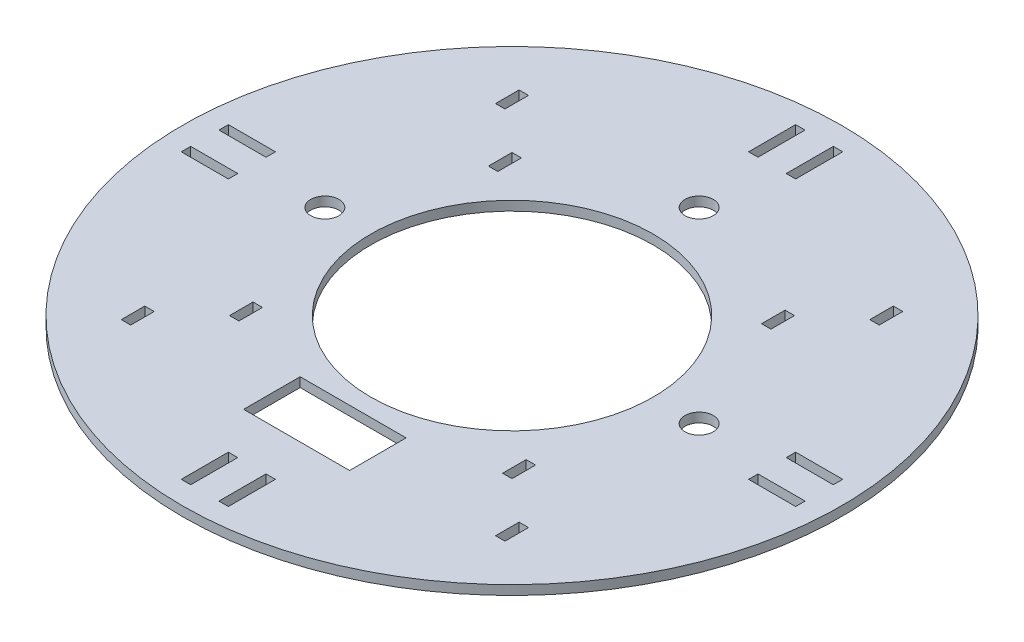
SolidWorks part; units mm, degrees
material "Thornel Mat VMA"
ref_plane "Front Plane" through (0, 0, 0) normal (0, 0, 1) x (1, 0, 0)
ref_plane "Top Plane" through (0, 0, 0) normal (0, 1, 0) x (1, 0, 0)
ref_plane "Right Plane" through (0, 0, 0) normal (1, 0, 0) x (0, 0, -1)
sketch "Sketch1" plane through (0, 0, 0) normal (0, 1, 0) x (1, 0, 0)
  line L0 (-49.4975, 49.4975) -> (-30, 30) construction
  line L1 (-52.2487, 5) -> (-67.2487, 5) construction
  line L2 (-67.2487, 5) -> (-67.2487, -5) construction
  line L3 (-67.2487, -5) -> (-52.2487, -5) construction
  line L4 (-52.2487, -5) -> (-52.2487, 5) construction
  line L5 (-30, -30) -> (30, 30) construction
  line L6 (-30, 30) -> (30, -30) construction
  line L7 (-30, 30) -> (-28, 30)
  line L8 (-30, 30) -> (-30, 25)
  line L9 (-30, 25) -> (-28, 25)
  line L10 (-28, 30) -> (-28, 25)
  line L11 (30, 30) -> (28, 30)
  line L12 (30, 30) -> (30, 25)
  line L13 (30, 25) -> (28, 25)
  line L14 (28, 30) -> (28, 25)
  line L15 (-30, -30) -> (-28, -30)
  line L16 (-30, -30) -> (-30, -25)
  line L17 (-30, -25) -> (-28, -25)
  line L18 (-28, -30) -> (-28, -25)
  line L19 (30, -30) -> (28, -30)
  line L20 (30, -30) -> (30, -25)
  line L21 (30, -25) -> (28, -25)
  line L22 (28, -30) -> (28, -25)
  line L23 (30, 30) -> (49.4975, 49.4975) construction
  line L24 (-49.4975, -49.4975) -> (-30, -30) construction
  line L25 (-30, -30) -> (-30, 30) construction
  line L26 (-30, 30) -> (30, 30) construction
  line L27 (30, 30) -> (30, -30) construction
  line L28 (30, -30) -> (30.057, -29.7836) construction
  line L29 (49.4975, -49.4975) -> (30, -30) construction
  line L30 (0, 49.4975) -> (0, 70) construction
  line L31 (-40.7487, 42.2487) -> (-38.7487, 42.2487)
  line L32 (-40.7487, 42.2487) -> (-40.7487, 37.2487)
  line L33 (-40.7487, 37.2487) -> (-38.7487, 37.2487)
  line L34 (-38.7487, 42.2487) -> (-38.7487, 37.2487)
  line L35 (-40.7487, 42.2487) -> (-38.7487, 37.2487) construction
  line L36 (-40.7487, 37.2487) -> (-38.7487, 42.2487) construction
  line L37 (38.7487, 42.2487) -> (40.7487, 42.2487)
  line L38 (38.7487, 42.2487) -> (38.7487, 37.2487)
  line L39 (38.7487, 37.2487) -> (40.7487, 37.2487)
  line L40 (40.7487, 42.2487) -> (40.7487, 37.2487)
  line L41 (38.7487, 42.2487) -> (40.7487, 37.2487) construction
  line L42 (38.7487, 37.2487) -> (40.7487, 42.2487) construction
  line L43 (38.7487, -37.2487) -> (40.7487, -37.2487)
  line L44 (38.7487, -37.2487) -> (38.7487, -42.2487)
  line L45 (38.7487, -42.2487) -> (40.7487, -42.2487)
  line L46 (40.7487, -37.2487) -> (40.7487, -42.2487)
  line L47 (38.7487, -37.2487) -> (40.7487, -42.2487) construction
  line L48 (38.7487, -42.2487) -> (40.7487, -37.2487) construction
  line L49 (-40.7487, -37.2487) -> (-38.7487, -37.2487)
  line L50 (-40.7487, -37.2487) -> (-40.7487, -42.2487)
  line L51 (-40.7487, -42.2487) -> (-38.7487, -42.2487)
  line L52 (-38.7487, -37.2487) -> (-38.7487, -42.2487)
  line L53 (-40.7487, -37.2487) -> (-38.7487, -42.2487) construction
  line L54 (-40.7487, -42.2487) -> (-38.7487, -37.2487) construction
  line L55 (-49.4975, 0) -> (-70, 0) construction
  line L56 (49.4975, 0) -> (70, 0) construction
  line L57 (0, -49.4975) -> (0, -70) construction
  line L58 (-49.4975, 0) -> (-30, 0) construction
  line L60 (-11.25, -33.7487) -> (11.25, -33.7487)
  line L61 (-11.25, -33.7487) -> (-11.25, -45.7487)
  line L62 (-11.25, -45.7487) -> (11.25, -45.7487)
  line L63 (-5, 52.2487) -> (5, 67.2487) construction
  line L64 (-5, 67.2487) -> (5, 52.2487) construction
  line L65 (-5, 52.2487) -> (5, 52.2487) construction
  line L66 (5, 52.2487) -> (5, 67.2487) construction
  line L67 (5, 67.2487) -> (-5, 67.2487) construction
  line L68 (-5, 67.2487) -> (-5, 52.2487) construction
  line L69 (52.2487, -5) -> (67.2487, 5) construction
  line L70 (52.2487, 5) -> (67.2487, -5) construction
  line L71 (52.2487, -5) -> (67.2487, -5) construction
  line L72 (67.2487, -5) -> (67.2487, 5) construction
  line L73 (67.2487, 5) -> (52.2487, 5) construction
  line L74 (52.2487, 5) -> (52.2487, -5) construction
  line L75 (-5, -52.2487) -> (5, -67.2487) construction
  line L76 (-5, -67.2487) -> (5, -52.2487) construction
  line L77 (-5, -52.2487) -> (5, -52.2487) construction
  line L78 (5, -52.2487) -> (5, -67.2487) construction
  line L79 (5, -67.2487) -> (-5, -67.2487) construction
  line L80 (-5, -67.2487) -> (-5, -52.2487) construction
  line L81 (-67.2487, 5) -> (-52.2487, -5) construction
  line L82 (-67.2487, -5) -> (-52.2487, 5) construction
  line L83 (-67.2487, 5) -> (-62.2487, 5)
  line L84 (-67.2487, 5) -> (-67.2487, 3)
  line L85 (-67.2487, 3) -> (-62.2487, 3)
  line L86 (-62.2487, 5) -> (-62.2487, 3)
  line L87 (-67.2487, -5) -> (-62.2487, -5)
  line L88 (-67.2487, -5) -> (-67.2487, -3)
  line L89 (-67.2487, -3) -> (-62.2487, -3)
  line L90 (-62.2487, -5) -> (-62.2487, -3)
  line L91 (-52.2487, -5) -> (-57.2487, -5)
  line L92 (-52.2487, -5) -> (-52.2487, -3)
  line L93 (-52.2487, -3) -> (-57.2487, -3)
  line L94 (-57.2487, -5) -> (-57.2487, -3)
  line L95 (-52.2487, 5) -> (-57.2487, 5)
  line L96 (-52.2487, 5) -> (-52.2487, 3)
  line L97 (-52.2487, 3) -> (-57.2487, 3)
  line L98 (-57.2487, 5) -> (-57.2487, 3)
  line L99 (-5, 67.2487) -> (-3, 67.2487)
  line L100 (-5, 67.2487) -> (-5, 62.2487)
  line L101 (-5, 62.2487) -> (-3, 62.2487)
  line L102 (-3, 67.2487) -> (-3, 62.2487)
  line L103 (-5, 52.2487) -> (-3, 52.2487)
  line L104 (-5, 52.2487) -> (-5, 57.2487)
  line L105 (-5, 57.2487) -> (-3, 57.2487)
  line L106 (-3, 52.2487) -> (-3, 57.2487)
  line L107 (5, 52.2487) -> (3, 52.2487)
  line L108 (5, 52.2487) -> (5, 57.2487)
  line L109 (5, 57.2487) -> (3, 57.2487)
  line L110 (3, 52.2487) -> (3, 57.2487)
  line L111 (5, 67.2487) -> (3, 67.2487)
  line L112 (5, 67.2487) -> (5, 62.2487)
  line L113 (5, 62.2487) -> (3, 62.2487)
  line L114 (3, 67.2487) -> (3, 62.2487)
  line L115 (52.2487, 5) -> (57.2487, 5)
  line L116 (52.2487, 5) -> (52.2487, 3)
  line L117 (52.2487, 3) -> (57.2487, 3)
  line L118 (57.2487, 5) -> (57.2487, 3)
  line L119 (52.2487, -5) -> (57.2487, -5)
  line L120 (52.2487, -5) -> (52.2487, -3)
  line L121 (52.2487, -3) -> (57.2487, -3)
  line L122 (57.2487, -5) -> (57.2487, -3)
  line L123 (67.2487, 5) -> (62.2487, 5)
  line L124 (67.2487, 5) -> (67.2487, 3)
  line L125 (67.2487, 3) -> (62.2487, 3)
  line L126 (62.2487, 5) -> (62.2487, 3)
  line L127 (67.2487, -5) -> (62.2487, -5)
  line L128 (67.2487, -5) -> (67.2487, -3)
  line L129 (67.2487, -3) -> (62.2487, -3)
  line L130 (62.2487, -5) -> (62.2487, -3)
  line L131 (-5, -52.2487) -> (-3, -52.2487)
  line L132 (-5, -52.2487) -> (-5, -57.2487)
  line L133 (-5, -57.2487) -> (-3, -57.2487)
  line L134 (-3, -52.2487) -> (-3, -57.2487)
  line L135 (5, -52.2487) -> (3, -52.2487)
  line L136 (5, -52.2487) -> (5, -57.2487)
  line L137 (5, -57.2487) -> (3, -57.2487)
  line L138 (3, -52.2487) -> (3, -57.2487)
  line L139 (5, -67.2487) -> (3, -67.2487)
  line L140 (5, -67.2487) -> (5, -62.2487)
  line L141 (5, -62.2487) -> (3, -62.2487)
  line L142 (3, -67.2487) -> (3, -62.2487)
  line L143 (-5, -67.2487) -> (-3, -67.2487)
  line L144 (-5, -67.2487) -> (-5, -62.2487)
  line L145 (-5, -62.2487) -> (-3, -62.2487)
  line L146 (-3, -67.2487) -> (-3, -62.2487)
  line L147 (0, 49.4975) -> (0, 30) construction
  line L148 (30, 0) -> (49.4975, 0) construction
  line L149 (0, -30) -> (0, -49.4975) construction
  line L150 (-49.4975, -49.4975) -> (-49.4975, 49.4975) construction
  line L151 (-49.4975, 49.4975) -> (49.4975, 49.4975) construction
  line L152 (49.4975, 49.4975) -> (49.4975, -49.4975) construction
  line L153 (49.4975, -49.4975) -> (-49.4975, -49.4975) construction
  line L154 (-30, -30) -> (30, -30) construction
  line L155 (-52.2487, 5) -> (-67.2487, 5) construction
  line L156 (11.25, -33.7487) -> (11.25, -45.7487)
  line L157 (-11.25, -33.7487) -> (11.25, -45.7487) construction
  line L158 (-11.25, -45.7487) -> (11.25, -33.7487) construction
  circle A0 centre (0, 0) radius 30
  circle A1 centre (0, 0) radius 70
  circle A2 centre (0, -39.7487) radius 3
  circle A3 centre (39.7487, 0) radius 3
  circle A4 centre (-39.7487, 0) radius 3
  circle A5 centre (0, 39.7487) radius 3
  point P20 (-39.7487, 39.7487)
  point P29 (39.7487, 39.7487)
  point P34 (39.7487, -39.7487)
  point P39 (-39.7487, -39.7487)
  point P52 (0, 59.7487)
  point P57 (59.7487, 0)
  point P62 (0, -59.7487)
  point P67 (-59.7487, 0)
  dimension "D1" = 60
  dimension "D2" = 140
  dimension "D65" = 6
  dimension "D66" = 6
  dimension "D67" = 6
  dimension "D68" = 6
  dimension "D3" = 60
  dimension "D4" = 60
  dimension "D5" = 5
  dimension "D6" = 2
  dimension "D7" = 5
  dimension "D8" = 2
  dimension "D9" = 2
  dimension "D10" = 5
  dimension "D11" = 2
  dimension "D12" = 5
  dimension "D13" = 5
  dimension "D14" = 2
  dimension "D15" = 5
  dimension "D16" = 2
  dimension "D17" = 2
  dimension "D18" = 5
  dimension "D19" = 2
  dimension "D20" = 5
  dimension "D21" = 20.5025
  dimension "D22" = 15
  dimension "D23" = 10
  dimension "D24" = 20.5025
  dimension "D25" = 15
  dimension "D26" = 10
  dimension "D27" = 20.5025
  dimension "D28" = 15
  dimension "D29" = 10
  dimension "D30" = 20.5025
  dimension "D31" = 15
  dimension "D32" = 10
  dimension "D33" = 5
  dimension "D34" = 2
  dimension "D35" = 5
  dimension "D36" = 2
  dimension "D37" = 5
  dimension "D38" = 2
  dimension "D39" = 5
  dimension "D40" = 5
  dimension "D41" = 5
  dimension "D42" = 5
  dimension "D43" = 5
  dimension "D44" = 2
  dimension "D45" = 2
  dimension "D46" = 2
  dimension "D47" = 2
  dimension "D48" = 5
  dimension "D49" = 5
  dimension "D50" = 5
  dimension "D51" = 5
  dimension "D52" = 2
  dimension "D53" = 2
  dimension "D54" = 2
  dimension "D55" = 2
  dimension "D56" = 2
  dimension "D57" = 5
  dimension "D58" = 5
  dimension "D59" = 2
  dimension "D60" = 2
  dimension "D61" = 2
  dimension "D62" = 5
  dimension "D63" = 5
  dimension "D64" = 2
  dimension "D69" = 19.4975
  dimension "D70" = 22.5
  dimension "D71" = 12
extrude "Yükseklik-Ekstrüzyon1" add sketch "Sketch1" along normal blind 2 contours A1 A5 A4 A3 L60 L156 L62 L61 L146 L143 L144 L145 L131 L134 L133 L132 L115 L118 L117 L116 L114 L111 L112 L113 L99 L102 L101 L100 L98 L95 L96 L97 L83 L86 L85 L84 L43 L46 L45
sketch "Sketch2" plane through (0, 2, 0) normal (0, 1, 0) x (1, 0, 0)
  line L0 (-52.2487, 5) -> (-52.2487, 21.5478)
  line L1 (-52.2487, 21.5478) -> (-52.2487, -8.4522)
  dimension "D1" = 30
sketch "Sketch3" plane through (0, 2, 0) normal (0, 1, 0) x (1, 0, 0)
  line L0 (-65.2487, 5) -> (-55.2487, 5)
  line L1 (-67.2487, 5) -> (-62.2487, 5) construction
  line L2 (-52.2487, 5) -> (-57.2487, 5) construction
  line L3 (-65.2487, 3) -> (-55.2487, 3)
  line L4 (-67.2487, 3) -> (-62.2487, 3) construction
  line L5 (-52.2487, 3) -> (-57.2487, 3) construction
  line L6 (-55.2487, 3) -> (-55.2487, 5)
  line L7 (-55.2487, 5) -> (-55.2081, 4.9702)
  line L8 (-65.2487, 3) -> (-65.2487, 5)
  line L10 (-55.2487, 5) -> (-52.2487, 5)
  line L11 (-55.2487, 5) -> (-55.2487, 3)
  line L12 (-55.2487, 3) -> (-52.2487, 3)
  line L13 (-52.2487, 5) -> (-52.2487, 3)
  line L14 (-65.2487, 5) -> (-67.2487, 5)
  line L15 (-65.2487, 5) -> (-65.2487, 3)
  line L16 (-65.2487, 3) -> (-67.2487, 3)
  line L17 (-67.2487, 5) -> (-67.2487, 3)
  dimension "D1" = 2
  dimension "D2" = 10
extrude "Boss-Extrude1" add sketch "Sketch3" against normal blind 2
sketch "Sketch5" plane through (0, 2, 0) normal (0, 1, 0) x (1, 0, 0)
  line L1 (-62.2487, 5) -> (-57.2487, 5)
  line L2 (-62.2487, 5) -> (-62.2487, 3)
  line L3 (-62.2487, 3) -> (-57.2487, 3)
  line L4 (-57.2487, 5) -> (-57.2487, 3)
extrude "Cut-Extrude1" cut sketch "Sketch5" against normal blind 2
sketch "Sketch6" plane through (0, 2, 0) normal (0, 1, 0) x (1, 0, 0)
  line L0 (-67.2487, -3) -> (-62.2487, -3) construction
  line L1 (-65.2487, -3) -> (-55.2487, -3)
  line L2 (-65.2487, -3) -> (-65.2487, -5)
  line L3 (-65.2487, -5) -> (-55.2487, -5)
  line L4 (-55.2487, -3) -> (-55.2487, -5)
  line L5 (-52.2487, -5) -> (-57.2487, -5) construction
  line L6 (-67.2487, -5) -> (-67.2487, -3) construction
  line L8 (-65.2487, -3) -> (-67.2487, -3)
  line L9 (-65.2487, -3) -> (-65.2487, -5)
  line L10 (-65.2487, -5) -> (-67.2487, -5)
  line L11 (-67.2487, -3) -> (-67.2487, -5)
  line L12 (-55.2487, -3) -> (-52.2487, -3)
  line L13 (-55.2487, -3) -> (-55.2487, -5)
  line L14 (-55.2487, -5) -> (-52.2487, -5)
  line L15 (-52.2487, -3) -> (-52.2487, -5)
  dimension "D1" = 10
  dimension "D2" = 2
extrude "Boss-Extrude3" add sketch "Sketch6" against normal blind 2 contours L8 L11 L10 L2 | L15 L12 L4 L14
sketch "Sketch8" plane through (0, 2, 0) normal (0, 1, 0) x (1, 0, 0)
  line L1 (-62.2487, -3) -> (-57.2487, -3)
  line L2 (-62.2487, -3) -> (-62.2487, -5)
  line L3 (-62.2487, -5) -> (-57.2487, -5)
  line L4 (-57.2487, -3) -> (-57.2487, -5)
extrude "Cut-Extrude2" cut sketch "Sketch8" against normal blind 2
sketch "Sketch9" plane through (0, 2, 0) normal (0, 1, 0) x (1, 0, 0)
  line L0 (3, 67.2487) -> (3, 62.2487) construction
  line L1 (3, 65.2487) -> (5, 65.2487)
  line L2 (3, 65.2487) -> (3, 55.2487)
  line L3 (3, 55.2487) -> (5, 55.2487)
  line L4 (5, 65.2487) -> (5, 55.2487)
  line L5 (5, 52.2487) -> (5, 57.2487) construction
  line L6 (5, 67.2487) -> (3, 67.2487) construction
  line L8 (5, 55.2487) -> (3, 55.2487)
  line L9 (5, 55.2487) -> (5, 52.2487)
  line L10 (5, 52.2487) -> (3, 52.2487)
  line L11 (3, 55.2487) -> (3, 52.2487)
  line L12 (5, 65.2487) -> (3, 65.2487)
  line L13 (5, 65.2487) -> (5, 67.2487)
  line L14 (5, 67.2487) -> (3, 67.2487)
  line L15 (3, 65.2487) -> (3, 67.2487)
  dimension "D1" = 2
  dimension "D2" = 10
extrude "Boss-Extrude4" add sketch "Sketch9" against normal blind 2 contours L15 L1 L13 L14 | L3 L11 L10 L9
sketch "Sketch10" plane through (0, 2, 0) normal (0, 1, 0) x (1, 0, 0)
  line L0 (-5, 67.2487) -> (-5, 62.2487) construction
  line L1 (3, 62.2487) -> (5, 62.2487)
  line L2 (3, 62.2487) -> (3, 57.2487)
  line L3 (3, 57.2487) -> (5, 57.2487)
  line L4 (5, 62.2487) -> (5, 57.2487)
  line L5 (-5, 65.2487) -> (-3, 65.2487)
  line L6 (-5, 65.2487) -> (-5, 55.2487)
  line L7 (-5, 55.2487) -> (-3, 55.2487)
  line L8 (-3, 65.2487) -> (-3, 55.2487)
  line L9 (-3, 52.2487) -> (-3, 57.2487) construction
  line L10 (-5, 67.2487) -> (-3, 67.2487) construction
  line L12 (-3, 55.2487) -> (-5, 55.2487)
  line L13 (-3, 55.2487) -> (-3, 52.2487)
  line L14 (-3, 52.2487) -> (-5, 52.2487)
  line L15 (-5, 55.2487) -> (-5, 52.2487)
  line L16 (-3, 65.2487) -> (-5, 65.2487)
  line L17 (-3, 65.2487) -> (-3, 67.2487)
  line L18 (-3, 67.2487) -> (-5, 67.2487)
  line L19 (-5, 65.2487) -> (-5, 67.2487)
  dimension "D1" = 2
  dimension "D2" = 10
extrude "Boss-Extrude5" add sketch "Sketch10" against normal blind 2 contours L19 L5 L17 L18 | L7 L15 L14 L13
sketch "Sketch12" plane through (0, 2, 0) normal (0, 1, 0) x (1, 0, 0)
  line L1 (-5, 62.2487) -> (-3, 62.2487)
  line L2 (-5, 62.2487) -> (-5, 57.2487)
  line L3 (-5, 57.2487) -> (-3, 57.2487)
  line L4 (-3, 62.2487) -> (-3, 57.2487)
extrude "Cut-Extrude4" cut sketch "Sketch12" against normal blind 2
sketch "Sketch13" plane through (0, 2, 0) normal (0, 1, 0) x (1, 0, 0)
  line L1 (5, 62.2487) -> (3, 62.2487)
  line L2 (5, 62.2487) -> (5, 57.2487)
  line L3 (5, 57.2487) -> (3, 57.2487)
  line L4 (3, 62.2487) -> (3, 57.2487)
extrude "Cut-Extrude5" cut sketch "Sketch13" against normal blind 2
sketch "Sketch14" plane through (0, 2, 0) normal (0, 1, 0) x (1, 0, 0)
  line L0 (67.2487, 5) -> (62.2487, 5) construction
  line L1 (65.2487, 5) -> (55.2487, 5)
  line L2 (65.2487, 5) -> (65.2487, 3)
  line L3 (65.2487, 3) -> (55.2487, 3)
  line L4 (55.2487, 5) -> (55.2487, 3)
  line L5 (52.2487, 3) -> (57.2487, 3) construction
  line L6 (67.2487, 5) -> (67.2487, 3) construction
  line L8 (52.2487, 5) -> (55.2487, 5)
  line L9 (52.2487, 5) -> (52.2487, 3)
  line L10 (52.2487, 3) -> (55.2487, 3)
  line L11 (55.2487, 5) -> (55.2487, 3)
  line L12 (65.2487, 5) -> (67.2487, 5)
  line L13 (65.2487, 5) -> (65.2487, 3)
  line L14 (65.2487, 3) -> (67.2487, 3)
  line L15 (67.2487, 5) -> (67.2487, 3)
  dimension "D1" = 2
  dimension "D2" = 10
extrude "Boss-Extrude6" add sketch "Sketch14" against normal blind 2 contours L9 L10 L4 L8 | L15 L12 L2 L14
sketch "Sketch15" plane through (0, 2, 0) normal (0, 1, 0) x (1, 0, 0)
  line L1 (57.2487, 5) -> (62.2487, 5)
  line L2 (57.2487, 5) -> (57.2487, 3)
  line L3 (57.2487, 3) -> (62.2487, 3)
  line L4 (62.2487, 5) -> (62.2487, 3)
extrude "Cut-Extrude6" cut sketch "Sketch15" against normal blind 2
sketch "Sketch16" plane through (0, 2, 0) normal (0, 1, 0) x (1, 0, 0)
  line L0 (67.2487, -3) -> (62.2487, -3) construction
  line L1 (65.2487, -3) -> (55.2487, -3)
  line L2 (65.2487, -3) -> (65.2487, -5)
  line L3 (65.2487, -5) -> (55.2487, -5)
  line L4 (55.2487, -3) -> (55.2487, -5)
  line L5 (52.2487, -5) -> (57.2487, -5) construction
  line L6 (67.2487, -5) -> (67.2487, -3) construction
  line L8 (65.2487, -3) -> (67.2487, -3)
  line L9 (65.2487, -3) -> (65.2487, -5)
  line L10 (65.2487, -5) -> (67.2487, -5)
  line L11 (67.2487, -3) -> (67.2487, -5)
  line L12 (55.2487, -3) -> (52.2487, -3)
  line L13 (55.2487, -3) -> (55.2487, -5)
  line L14 (55.2487, -5) -> (52.2487, -5)
  line L15 (52.2487, -3) -> (52.2487, -5)
  dimension "D1" = 2
  dimension "D2" = 10
extrude "Boss-Extrude9" add sketch "Sketch16" against normal blind 2 contours L12 L15 L14 L4 | L11 L8 L2 L10
sketch "Sketch17" plane through (0, 2, 0) normal (0, 1, 0) x (1, 0, 0)
  line L1 (57.2487, -3) -> (62.2487, -3)
  line L2 (57.2487, -3) -> (57.2487, -5)
  line L3 (57.2487, -5) -> (62.2487, -5)
  line L4 (62.2487, -3) -> (62.2487, -5)
extrude "Cut-Extrude7" cut sketch "Sketch17" against normal blind 2
sketch "Sketch18" plane through (0, 2, 0) normal (0, 1, 0) x (1, 0, 0)
  line L0 (-5, -67.2487) -> (-3, -67.2487) construction
  line L1 (3, -52.2487) -> (3, -57.2487) construction
  line L2 (3, -55.2487) -> (5, -55.2487)
  line L3 (3, -55.2487) -> (3, -65.2487)
  line L4 (3, -65.2487) -> (5, -65.2487)
  line L6 (-5, -52.2487) -> (-3, -52.2487)
  line L7 (-5, -67.2487) -> (-5, -62.2487) construction
  line L8 (-5, -65.2487) -> (-3, -65.2487)
  line L9 (-5, -65.2487) -> (-5, -55.2487)
  line L10 (-5, -55.2487) -> (-3, -55.2487)
  line L11 (-5, -52.2487) -> (-5, -55.2487)
  line L12 (-5, -55.2487) -> (-3, -55.2487)
  line L13 (-3, -52.2487) -> (-3, -55.2487)
  line L14 (5, -55.2487) -> (5, -65.2487)
  line L15 (5, -67.2487) -> (5, -62.2487) construction
  line L16 (5, -67.2487) -> (3, -67.2487) construction
  line L17 (-3, -65.2487) -> (-3, -55.2487)
  line L18 (-3, -52.2487) -> (-3, -57.2487) construction
  line L19 (3, -52.2487) -> (5, -52.2487)
  line L20 (3, -52.2487) -> (3, -55.2487)
  line L21 (3, -55.2487) -> (5, -55.2487)
  line L22 (5, -52.2487) -> (5, -55.2487)
  line L23 (5, -67.2487) -> (3, -67.2487)
  line L24 (5, -67.2487) -> (5, -65.2487)
  line L25 (5, -65.2487) -> (3, -65.2487)
  line L26 (3, -67.2487) -> (3, -65.2487)
  line L27 (-3, -67.2487) -> (-5, -67.2487)
  line L28 (-3, -67.2487) -> (-3, -65.2487)
  line L29 (-3, -65.2487) -> (-5, -65.2487)
  line L30 (-5, -67.2487) -> (-5, -65.2487)
  dimension "D1" = 2
  dimension "D2" = 10
  dimension "D3" = 2
  dimension "D4" = 10
extrude "Boss-Extrude10" add sketch "Sketch18" against normal blind 2 contours L13 L6 L11 L10 | L30 L27 L28 L8 | L26 L23 L24 L4 | L22 L19 L20 L2
sketch "Sketch19" plane through (0, 2, 0) normal (0, 1, 0) x (1, 0, 0)
  line L1 (3, -57.2487) -> (5, -57.2487)
  line L2 (3, -57.2487) -> (3, -62.2487)
  line L3 (3, -62.2487) -> (5, -62.2487)
  line L4 (5, -57.2487) -> (5, -62.2487)
  line L5 (-3, -57.2487) -> (-5, -57.2487)
  line L6 (-3, -57.2487) -> (-3, -62.2487)
  line L7 (-3, -62.2487) -> (-5, -62.2487)
  line L8 (-5, -57.2487) -> (-5, -62.2487)
extrude "Cut-Extrude8" cut sketch "Sketch19" against normal blind 2
